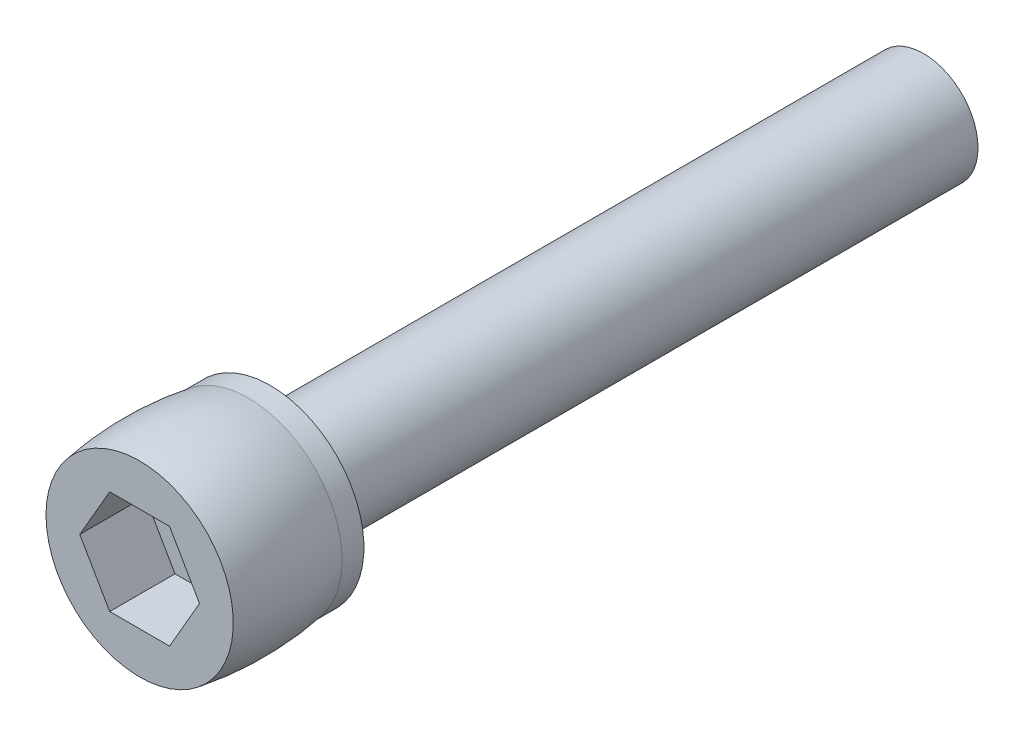
SolidWorks part; units mm, degrees
ref_plane "Front Plane" through (0, 0, 0) normal (0, 0, 1) x (1, 0, 0)
ref_plane "Top Plane" through (0, 0, 0) normal (0, 1, 0) x (1, 0, 0)
ref_plane "Right Plane" through (0, 0, 0) normal (1, 0, 0) x (0, 0, -1)
sketch "Sketch1" plane through (0, 0, 0) normal (0, 0, 1) x (1, 0, 0)
  circle A0 centre (0, 0) radius 1.25
extrude "Boss-Extrude1" add sketch "Sketch1" against normal blind 15
sketch "Sketch2" plane through (0, 0, 0) normal (0, 0, 1) x (1, 0, 0)
  circle A0 centre (0, 0) radius 2.25
extrude "Boss-Extrude2" add sketch "Sketch2" along normal blind 3
sketch "Sketch3" plane through (0, 0, 0) normal (1, 0, 0) x (0, 0, -1)
  line L0 (-3, 2.15) -> (-3, 2.75)
  line L1 (-3, 2.25) -> (-3, -2.25) construction
  line L2 (-3, 2.75) -> (0, 2.75)
  line L3 (-0.5, 2.15) -> (0, 2.15)
  line L4 (0, -2.25) -> (0, 2.25) construction
  line L5 (0, 2.15) -> (0, 2.75)
  line L8 (-3, 0) -> (-4.0042, 0)
  arc A1 (-0.5, 2.15) -> (-3, 2.15) centre (-1.75, -5.6125) ccw
  dimension "D3" = 0.5
  dimension "D4" = 2.15
revolve "Cut-Revolve1" cut sketch "Sketch3" angle 360 about L8
sketch "Sketch4" plane through (0, 0, 3) normal (0, 0, 1) x (1, 0, 0)
  line L1 (1.3748, 0) -> (0.6874, 1.1906)
  line L2 (0.6874, 1.1906) -> (-0.6874, 1.1906)
  line L3 (-0.6874, 1.1906) -> (-1.3748, 0)
  line L4 (-1.3748, 0) -> (-0.6874, -1.1906)
  line L5 (-0.6874, -1.1906) -> (0.6874, -1.1906)
  line L6 (0.6874, -1.1906) -> (1.3748, 0)
  circle A0 centre (0, 0) radius 1.1906 construction
extrude "Cut-Extrude1" cut sketch "Sketch4" against normal blind 1.5
